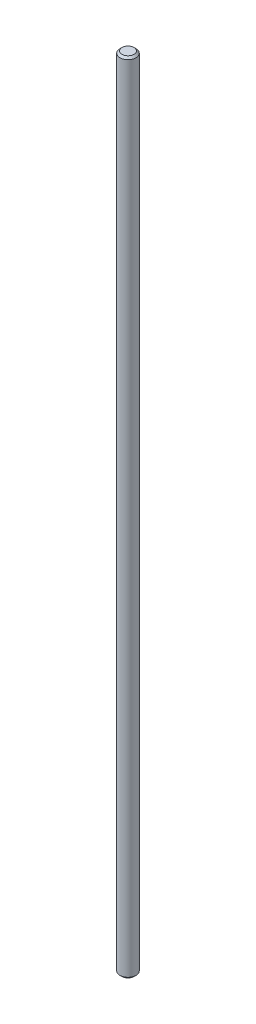
SolidWorks part; units mm, degrees
material "AISI 1020"
ref_plane "Front Plane" through (0, 0, 0) normal (0, 0, 1) x (1, 0, 0)
ref_plane "Top Plane" through (0, 0, 0) normal (0, 1, 0) x (1, 0, 0)
ref_plane "Right Plane" through (0, 0, 0) normal (1, 0, 0) x (0, 0, -1)
sketch "Sketch1" plane through (0, 0, 0) normal (0, 1, 0) x (1, 0, 0)
  circle A0 centre (0, 0) radius 2
  dimension "D1" = 4
extrude "Boss-Extrude1" add sketch "Sketch1" along normal mid plane 200
chamfer "Chamfer1" distance 0.5 angle 45 2 edges at (0, -100, 2) (0, 100, 2)
